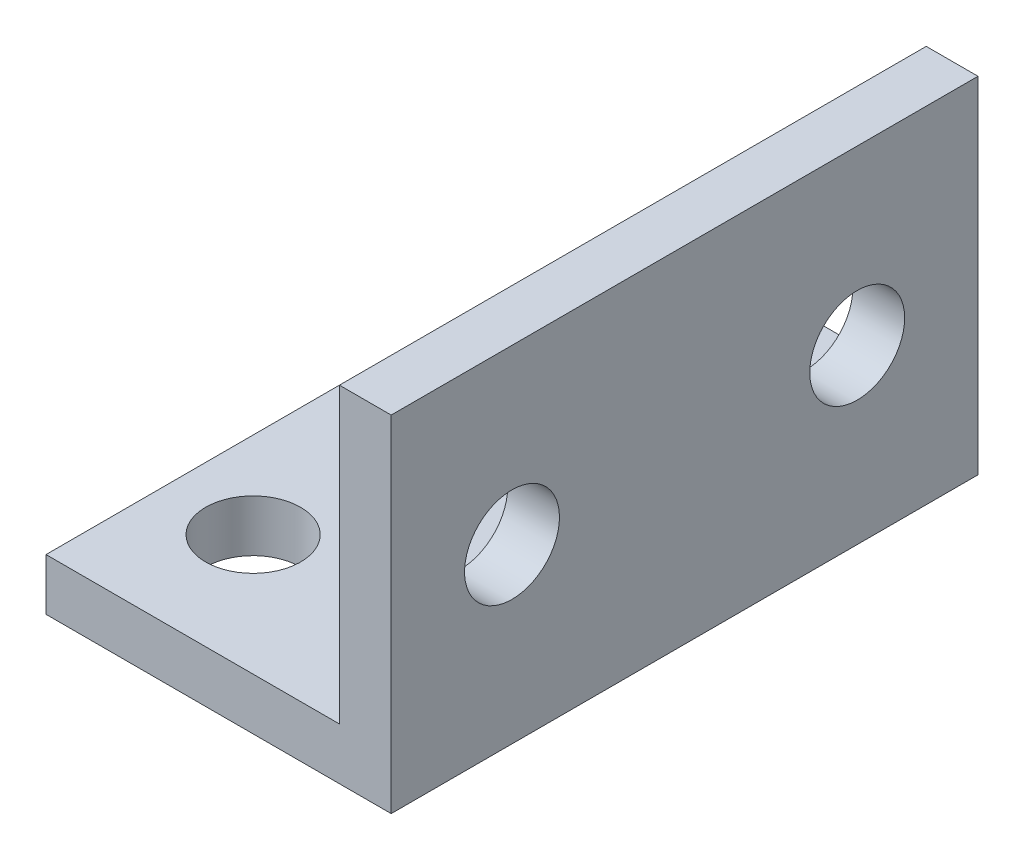
SolidWorks part; units mm, degrees
ref_plane "正面" through (0, 0, 0) normal (0, 0, 1) x (1, 0, 0)
ref_plane "平面" through (0, 0, 0) normal (0, 1, 0) x (1, 0, 0)
ref_plane "右側面" through (0, 0, 0) normal (1, 0, 0) x (0, 0, -1)
sketch "ｽｹｯﾁ1" plane through (0, 0, 0) normal (0, 0, 1) x (1, 0, 0)
  line L0 (0, 0) -> (17, 0)
  line L1 (17, 0) -> (17, 17)
  line L2 (0, -3) -> (20, -3)
  line L3 (20, -3) -> (20, 17)
  line L4 (0, 0) -> (0, -3)
  line L5 (17, 17) -> (20, 17)
  point P7 (23, -3)
  dimension "D1" = 20
  dimension "D2" = 20
  dimension "D3" = 3
extrude "ﾎﾞｽ - 押し出し1" add sketch "ｽｹｯﾁ1" along normal blind 34
sketch "ｽｹｯﾁ2" plane through (20, 0, 0) normal (1, 0, 0) x (0, 0, -1)
  line L0 (-34, 7) -> (0, 7) construction
  line L1 (-34, -3) -> (-34, 17) construction
  line L2 (0, -3) -> (0, 17) construction
  circle A0 centre (-27, 7) radius 2.75
  circle A1 centre (-7, 7) radius 2.75
  dimension "D1" = 5.5
  dimension "D2" = 7
  dimension "D3" = 7
extrude "ｶｯﾄ - 押し出し1" cut sketch "ｽｹｯﾁ2" against normal through all
sketch "ｽｹｯﾁ3" plane through (0, -3, 0) normal (0, -1, 0) x (1, 0, 0)
  line L0 (5, 0) -> (5, 34) construction
  line L1 (0, 0) -> (20, 0) construction
  line L2 (0, 34) -> (20, 34) construction
  line L3 (20, 34) -> (20, 0) construction
  circle A0 centre (5, 7) radius 2.75
  circle A1 centre (5, 27) radius 2.75
  dimension "D2" = 7
  dimension "D3" = 7
  dimension "D4" = 5.5
  dimension "D1" = 15
extrude "ｶｯﾄ - 押し出し2" cut sketch "ｽｹｯﾁ3" against normal through all
